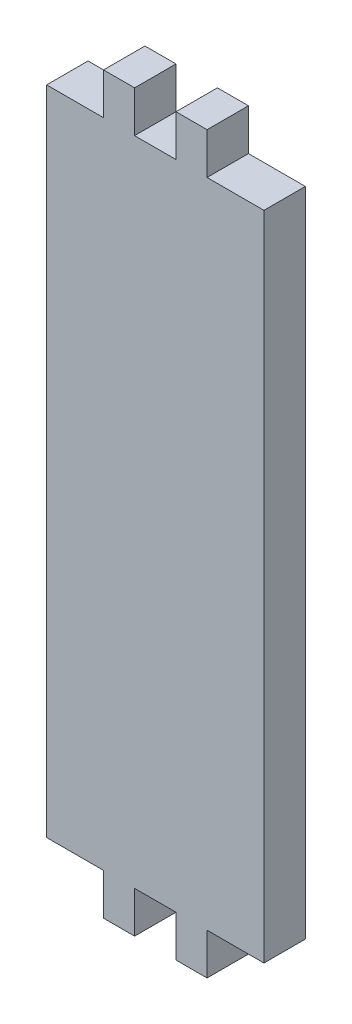
SolidWorks part; units mm, degrees
ref_plane "Front Plane" through (0, 0, 0) normal (0, 0, 1) x (1, 0, 0)
ref_plane "Top Plane" through (0, 0, 0) normal (0, 1, 0) x (1, 0, 0)
ref_plane "Right Plane" through (0, 0, 0) normal (1, 0, 0) x (0, 0, -1)
sketch "Sketch1" plane through (0, 0, 0) normal (0, 0, 1) x (1, 0, 0)
  line L1 (-10.0604, 28.2194) -> (16.5996, 28.2194)
  line L2 (-10.0604, 28.2194) -> (-10.0604, -51.7606)
  line L3 (-10.0604, -51.7606) -> (16.5996, -51.7606)
  line L4 (16.5996, 28.2194) -> (16.5996, -51.7606)
  dimension "D1" = 79.98
  dimension "D2" = 26.66
extrude "Boss-Extrude1" add sketch "Sketch1" along normal blind 5.08
sketch "Sketch2" plane through (0, 0, 5.08) normal (0, 0, 1) x (1, 0, 0)
  line L0 (3.2696, 28.2194) -> (3.2696, -51.7606) construction
  line L1 (16.5996, 28.2194) -> (-10.0604, 28.2194) construction
  line L2 (-10.0604, -51.7606) -> (16.5996, -51.7606) construction
  line L3 (16.5996, -11.7706) -> (-10.0604, -11.7706) construction
  line L4 (16.5996, -51.7606) -> (16.5996, 28.2194) construction
  line L5 (-10.0604, 28.2194) -> (-10.0604, -51.7606) construction
  line L6 (-3.0804, -51.7606) -> (-3.0804, -56.8406)
  line L7 (5.8096, 28.2194) -> (9.6196, 28.2194)
  line L8 (5.8096, 28.2194) -> (5.8096, 33.2994)
  line L9 (5.8096, 33.2994) -> (9.6196, 33.2994)
  line L10 (9.6196, 28.2194) -> (9.6196, 33.2994)
  line L11 (0.7296, 28.2194) -> (-3.0804, 28.2194)
  line L12 (0.7296, 28.2194) -> (0.7296, 33.2994)
  line L13 (0.7296, 33.2994) -> (-3.0804, 33.2994)
  line L14 (-3.0804, 28.2194) -> (-3.0804, 33.2994)
  line L15 (0.7296, -56.8406) -> (-3.0804, -56.8406)
  line L16 (0.7296, -51.7606) -> (0.7296, -56.8406)
  line L17 (0.7296, -51.7606) -> (-3.0804, -51.7606)
  line L18 (9.6196, -51.7606) -> (9.6196, -56.8406)
  line L19 (5.8096, -56.8406) -> (9.6196, -56.8406)
  line L20 (5.8096, -51.7606) -> (5.8096, -56.8406)
  line L21 (5.8096, -51.7606) -> (9.6196, -51.7606)
  dimension "D1" = 3.81
  dimension "D2" = 3.81
  dimension "D3" = 2.54
  dimension "D4" = 2.54
  dimension "D5" = 5.08
  dimension "D6" = 5.08
extrude "Boss-Extrude2" add sketch "Sketch2" against normal blind 5.08
sketch "Sketch3" plane through (0, 0, 5.08) normal (0, 0, 1) x (1, 0, 0)
  line L1 (-10.0604, 28.2194) -> (-10.0604, -51.7606) construction
  line L2 (16.5996, -51.7606) -> (16.5996, 28.2194) construction
  line L3 (-10.0604, 1.5594) -> (16.5996, 1.5594)
  line L4 (16.5996, -25.1006) -> (-10.0604, -25.1006)
  line L5 (9.6196, -51.7606) -> (16.5996, -51.7606) construction
  dimension "D1" = 26.66
  dimension "D2" = 26.66
